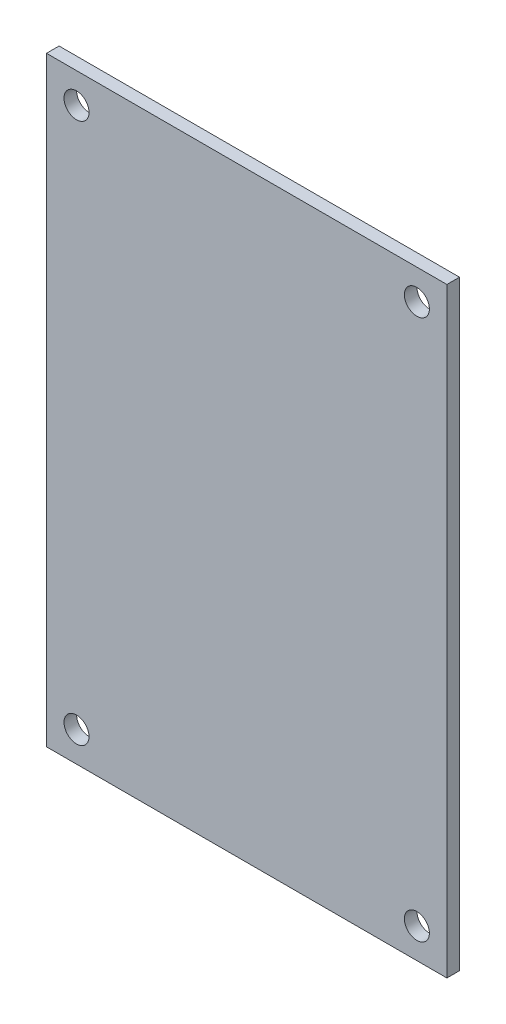
SolidWorks part; units mm, degrees
ref_plane "Front Plane" through (0, 0, 0) normal (0, 0, 1) x (1, 0, 0)
ref_plane "Top Plane" through (0, 0, 0) normal (0, 1, 0) x (1, 0, 0)
ref_plane "Right Plane" through (0, 0, 0) normal (1, 0, 0) x (0, 0, -1)
sketch "Sketch1" plane through (0, 0, 0) normal (0, 0, 1) x (1, 0, 0)
  line L1 (25.4, -38.1) -> (-25.4, -38.1)
  line L2 (25.4, -38.1) -> (25.4, 38.1)
  line L3 (25.4, 38.1) -> (-25.4, 38.1)
  line L4 (-25.4, -38.1) -> (-25.4, 38.1)
  line L5 (25.4, -38.1) -> (-25.4, 38.1) construction
  line L6 (25.4, 38.1) -> (-25.4, -38.1) construction
  point P0 (0, 0)
  dimension "D1" = 50.8
  dimension "D2" = 76.2
extrude "Boss-Extrude1" add sketch "Sketch1" along normal blind 1.6002
sketch "Sketch2" plane through (0, 0, 1.6002) normal (0, 0, 1) x (1, 0, 0)
  line L0 (25.4, 38.1) -> (-25.4, 38.1) construction
  line L1 (-25.4, 38.1) -> (-25.4, -38.1) construction
  line L2 (0, -0.8801) -> (0, 0.8801) construction
  line L3 (0.8801, 0) -> (-0.8801, 0) construction
  circle A0 centre (-21.59, 34.29) radius 1.5875
  circle A2 centre (21.59, 34.29) radius 1.5875
  circle A3 centre (21.59, -34.29) radius 1.5875
  circle A4 centre (-21.59, -34.29) radius 1.5875
  point P4 (0, 0)
  point P5 (-19.896, 33.3551)
  dimension "D1" = 3.175
  dimension "D2" = 3.81
  dimension "D3" = 3.81
extrude "Cut-Extrude1" cut sketch "Sketch2" against normal up to next
